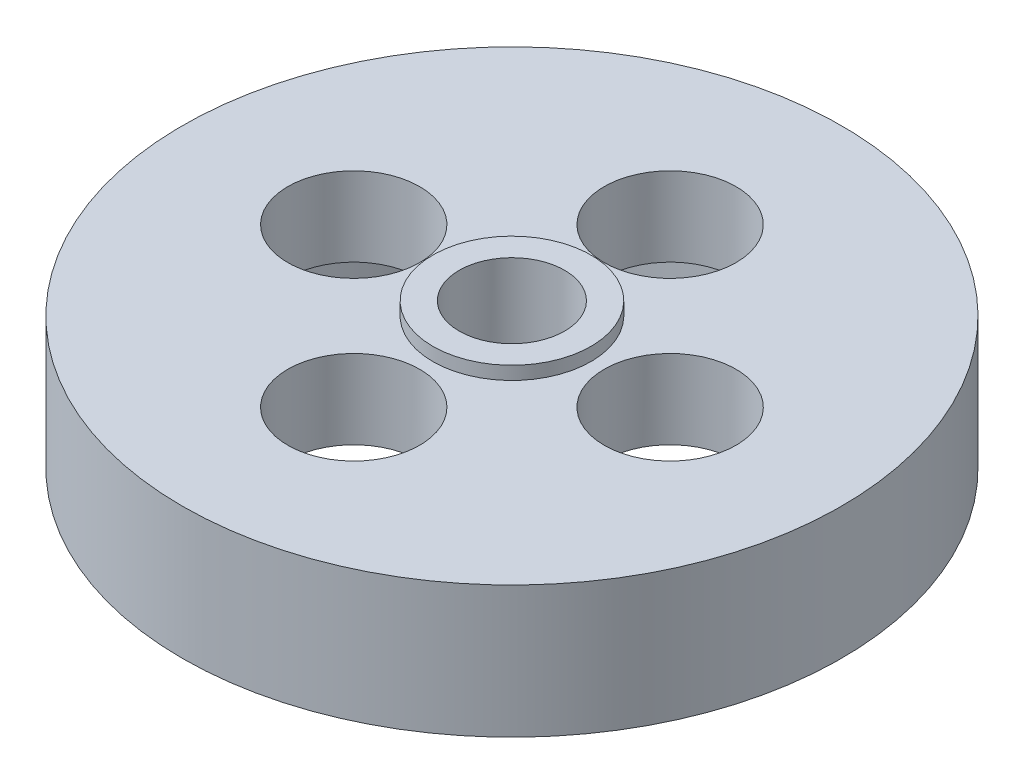
SolidWorks part; units mm, degrees
ref_plane "Front Plane" through (0, 0, 0) normal (0, 0, 1) x (1, 0, 0)
ref_plane "Top Plane" through (0, 0, 0) normal (0, 1, 0) x (1, 0, 0)
ref_plane "Right Plane" through (0, 0, 0) normal (1, 0, 0) x (0, 0, -1)
sketch "Sketch1" plane through (0, 0, 0) normal (0, 1, 0) x (1, 0, 0)
  circle A0 centre (0, 0) radius 25
  circle A1 centre (0, 0) radius 12
  dimension "D1" = 50
  dimension "D2" = 24
extrude "Boss-Extrude1" add sketch "Sketch1" along normal blind 10 contours A0
sketch "Sketch2" plane through (0, 10, 0) normal (0, 1, 0) x (1, 0, 0)
  circle A0 centre (0, 0) radius 12
  circle A1 centre (12, 0) radius 5
  dimension "D1" = 24
  dimension "D2" = 10
extrude "Cut-Extrude1" cut sketch "Sketch2" against normal blind 10 contours A1
sketch "Sketch3" plane through (0, 10, 0) normal (0, 1, 0) x (1, 0, 0)
  circle A0 centre (0, 0) radius 4
  dimension "D1" = 8
extrude "Cut-Extrude2" cut sketch "Sketch3" against normal blind 10
pattern_circular "CirPattern1" count 4 over 360 about axis through (0, 0, 0) along (0, 1, 0) of "Cut-Extrude1"
sketch "Sketch6" plane through (0, 0, 0) normal (0, -1, 0) x (1, 0, 0)
  circle A0 centre (0, 0) radius 18
  dimension "D1" = 36
extrude "Cut-Extrude4" cut sketch "Sketch6" against normal blind 4
sketch "Sketch7" plane through (0, 10, 0) normal (0, 1, 0) x (1, 0, 0)
  circle A0 centre (0, 0) radius 6
  dimension "D1" = 12
extrude "Boss-Extrude2" add sketch "Sketch7" along normal blind 1
sketch "Sketch8" plane through (0, 0, 0) normal (0, -1, 0) x (1, 0, 0)
  circle A0 centre (0, 0) radius 4
extrude "Cut-Extrude5" cut sketch "Sketch8" against normal blind 20
